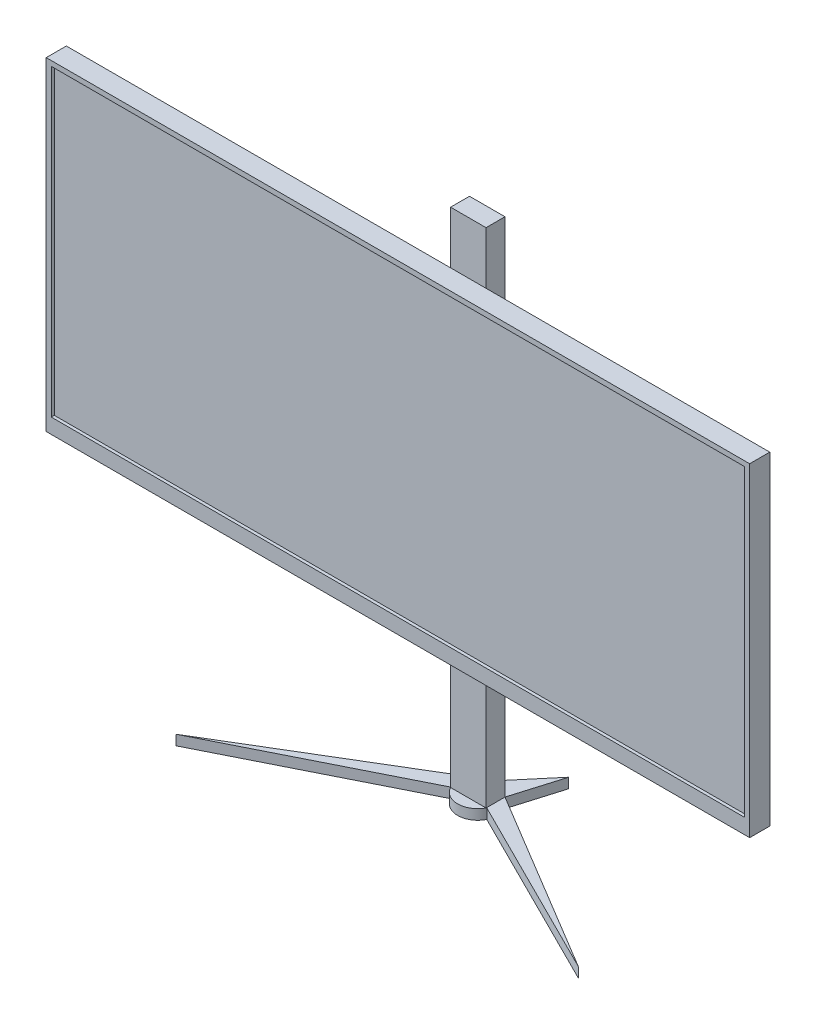
SolidWorks part; units mm, degrees
ref_plane "Front Plane" through (0, 0, 0) normal (0, 0, 1) x (1, 0, 0)
ref_plane "Top Plane" through (0, 0, 0) normal (0, 1, 0) x (1, 0, 0)
ref_plane "Right Plane" through (0, 0, 0) normal (1, 0, 0) x (0, 0, -1)
sketch "Sketch1" plane through (0, 0, 0) normal (0, 1, 0) x (1, 0, 0)
  line L0 (0, 0) -> (400, 0) construction
  line L1 (200, 0) -> (200, 100) construction
  line L2 (0, 0) -> (182.1115, 91.0557)
  line L3 (217.8885, 91.0557) -> (400, 0)
  line L4 (182.3529, 109.4118) -> (0, 0)
  line L5 (217.6471, 109.4118) -> (400, 0)
  line L6 (200, 120) -> (167.7854, 158.239)
  line L7 (182.3529, 109.4118) -> (167.7854, 158.239)
  line L8 (200, 120) -> (232.2146, 158.239)
  line L9 (217.6471, 109.4118) -> (232.2146, 158.239)
  arc A1 (182.1115, 91.0557) -> (217.8885, 91.0557) centre (200, 100) ccw
  dimension "D3" = 20
  dimension "D1" = 400
  dimension "D2" = 100
  dimension "D4" = 50
extrude "Boss-Extrude1" add sketch "Sketch1" along normal blind 10
sketch "Sketch6" plane through (0, 10, 0) normal (0, 1, 0) x (1, 0, 0)
  line L0 (200, 80) -> (200, 120) construction
  line L2 (182.3529, 90.5882) -> (217.6471, 90.5882)
  line L3 (182.3529, 90.5882) -> (182.3529, 109.4118)
  line L4 (182.3529, 109.4118) -> (217.6471, 109.4118)
  line L5 (217.6471, 90.5882) -> (217.6471, 109.4118)
  line L6 (182.3529, 90.5882) -> (217.6471, 109.4118) construction
  line L7 (182.3529, 109.4118) -> (217.6471, 90.5882) construction
  arc A0 (182.1115, 91.0557) -> (217.8885, 91.0557) centre (200, 100) ccw construction
  point P6 (200, 100)
extrude "Boss-Extrude3" add sketch "Sketch6" along normal blind 500
sketch "Sketch8" plane through (0, 0, -90.5882) normal (0, 0, 1) x (1, 0, 0)
  line L0 (217.6471, 510) -> (217.6471, 10) construction
  line L1 (217.6471, 356.7521) -> (182.3529, 356.7521)
  line L2 (217.6471, 356.7521) -> (217.6471, 336.5181)
  line L3 (217.6471, 336.5181) -> (182.3529, 336.5181)
  line L4 (182.3529, 356.7521) -> (182.3529, 336.5181)
  line L5 (182.3529, 510) -> (182.3529, 10) construction
extrude "Boss-Extrude4" add sketch "Sketch8" along normal blind 50
sketch "Sketch9" plane through (0, 0, -40.5882) normal (0, 0, 1) x (1, 0, 0)
  line L0 (182.3529, 346.6351) -> (217.6471, 346.6351) construction
  line L1 (182.3529, 356.7521) -> (182.3529, 336.5181) construction
  line L2 (217.6471, 336.5181) -> (217.6471, 356.7521) construction
  line L4 (-149.9, 185.5351) -> (549.9, 185.5351)
  line L5 (-149.9, 185.5351) -> (-149.9, 507.7351)
  line L6 (-149.9, 507.7351) -> (549.9, 507.7351)
  line L7 (549.9, 185.5351) -> (549.9, 507.7351)
  line L8 (-149.9, 185.5351) -> (549.9, 507.7351) construction
  line L9 (-149.9, 507.7351) -> (549.9, 185.5351) construction
  point P6 (200, 346.6351)
  dimension "D1" = 322.2
  dimension "D2" = 699.8
extrude "Boss-Extrude5" add sketch "Sketch9" along normal blind 20
sketch "Sketch10" plane through (0, 0, -20.5882) normal (0, 0, 1) x (1, 0, 0)
  line L0 (-149.9, 185.5351) -> (-149.9, 200.5351) construction
  line L1 (-149.9, 507.7351) -> (-149.9, 185.5351) construction
  line L2 (549.9, 185.5351) -> (549.9, 200.5351) construction
  line L3 (549.9, 185.5351) -> (549.9, 507.7351) construction
  line L4 (-149.9, 507.7351) -> (-144.9, 507.7351) construction
  line L5 (549.9, 507.7351) -> (-149.9, 507.7351) construction
  line L6 (-149.9, 507.7351) -> (-149.9, 502.7351) construction
  line L7 (549.9, 507.7351) -> (544.9, 507.7351) construction
  line L8 (549.9, 507.7351) -> (549.9, 502.7351) construction
  line L10 (544.9, 502.7351) -> (-144.9, 502.7351)
  line L11 (544.9, 502.7351) -> (544.9, 200.5351)
  line L12 (544.9, 200.5351) -> (-144.9, 200.5351)
  line L13 (-144.9, 502.7351) -> (-144.9, 200.5351)
  dimension "D1" = 15
  dimension "D2" = 5
  dimension "D3" = 5
  dimension "D4" = 5
extrude "Cut-Extrude1" cut sketch "Sketch10" against normal blind 3
sketch "Sketch11" plane through (0, 0, -40.5882) normal (0, 0, -1) x (-1, 0, 0)
  line L0 (-549.9, 185.5351) -> (-217.6471, 185.5351) construction
  line L1 (-217.6471, 510) -> (-217.6471, 10) construction
  line L2 (149.9, 185.5351) -> (-549.9, 185.5351) construction
  line L3 (-383.7735, 185.5351) -> (-383.7735, 215.5351) construction
  line L4 (-433.7735, 215.5351) -> (-333.7735, 215.5351)
  line L7 (-433.7735, 245.5351) -> (-433.7735, 215.5351)
  line L8 (-413.3535, 225.5351) -> (-403.3535, 225.5351) construction
  line L9 (-422.7735, 227.9551) -> (-414.3535, 227.9551)
  line L10 (-423.7735, 226.9551) -> (-423.7735, 225.5351)
  line L11 (-423.7735, 225.5351) -> (-413.3535, 225.5351)
  line L12 (-413.3535, 226.9551) -> (-413.3535, 225.5351)
  line L13 (-408.3535, 225.5351) -> (-408.3535, 227.9551) construction
  line L14 (-422.7735, 227.9551) -> (-423.7735, 226.9551)
  line L15 (-414.3535, 227.9551) -> (-413.3535, 226.9551)
  line L16 (-392.9335, 225.5351) -> (-403.3535, 225.5351)
  line L17 (-403.3535, 226.9551) -> (-403.3535, 225.5351)
  line L18 (-402.3535, 227.9551) -> (-403.3535, 226.9551)
  line L19 (-393.9335, 227.9551) -> (-402.3535, 227.9551)
  line L20 (-393.9335, 227.9551) -> (-392.9335, 226.9551)
  line L21 (-392.9335, 226.9551) -> (-392.9335, 225.5351)
  line L22 (-392.9335, 225.5351) -> (-382.9335, 225.5351) construction
  line L23 (-382.9335, 225.5351) -> (-366.8335, 225.5351)
  line L24 (-366.8335, 225.5351) -> (-366.8335, 229.2951)
  line L25 (-367.8335, 230.2951) -> (-382.9335, 230.2951)
  line L26 (-382.9335, 230.2951) -> (-382.9335, 225.5351)
  line L27 (-366.8335, 225.5351) -> (-356.8335, 225.5351) construction
  line L28 (-361.8335, 225.5351) -> (-361.8335, 230.2951) construction
  line L29 (-356.8335, 230.2951) -> (-341.7335, 230.2951)
  line L30 (-356.8335, 225.5351) -> (-356.8335, 230.2951)
  line L31 (-340.7335, 225.5351) -> (-356.8335, 225.5351)
  line L32 (-340.7335, 229.2951) -> (-340.7335, 225.5351)
  line L33 (-366.8335, 229.2951) -> (-367.8335, 230.2951)
  line L34 (-341.7335, 230.2951) -> (-340.7335, 229.2951)
  line L35 (-433.7735, 245.5351) -> (-333.7735, 245.5351)
  line L36 (-333.7735, 245.5351) -> (-333.7735, 215.5351)
  point P9 (-383.7735, 215.5351)
  point P14 (-423.7735, 227.9551)
  point P17 (-413.3535, 227.9551)
  point P33 (-366.8335, 230.2951)
  point P38 (-340.7335, 230.2951)
  dimension "D1" = 30
  dimension "D2" = 30
  dimension "D4" = 10
  dimension "D5" = 10
  dimension "D6" = 2.42
  dimension "D7" = 10.42
  dimension "D8" = 10
  dimension "D9" = 16.1
  dimension "D12" = 4.76
  dimension "D13" = 10
extrude "Cut-Extrude6" cut sketch "Sketch11" against normal blind 5 contours L21 L20 L19 L18 L17 L16 | L24 L33 L25 L26 L23 | L34 L29 L30 L31 L32 | L10 L14 L9 L15 L12 L11
sketch "Sketch13" plane through (0, 0, -40.5882) normal (0, 0, -1) x (-1, 0, 0)
  line L0 (-549.9, 185.5351) -> (-549.9, 507.7351) construction
  line L1 (-429.9, 214.0972) -> (-329.9, 214.0972)
  line L2 (-429.9, 214.0972) -> (-429.9, 234.0972)
  line L3 (-429.9, 234.0972) -> (-329.9, 234.0972)
  line L4 (-329.9, 214.0972) -> (-329.9, 234.0972)
  dimension "D1" = 20
  dimension "D2" = 100
  dimension "D3" = 120
extrude "Cut-Extrude7" cut sketch "Sketch13" against normal blind 2
